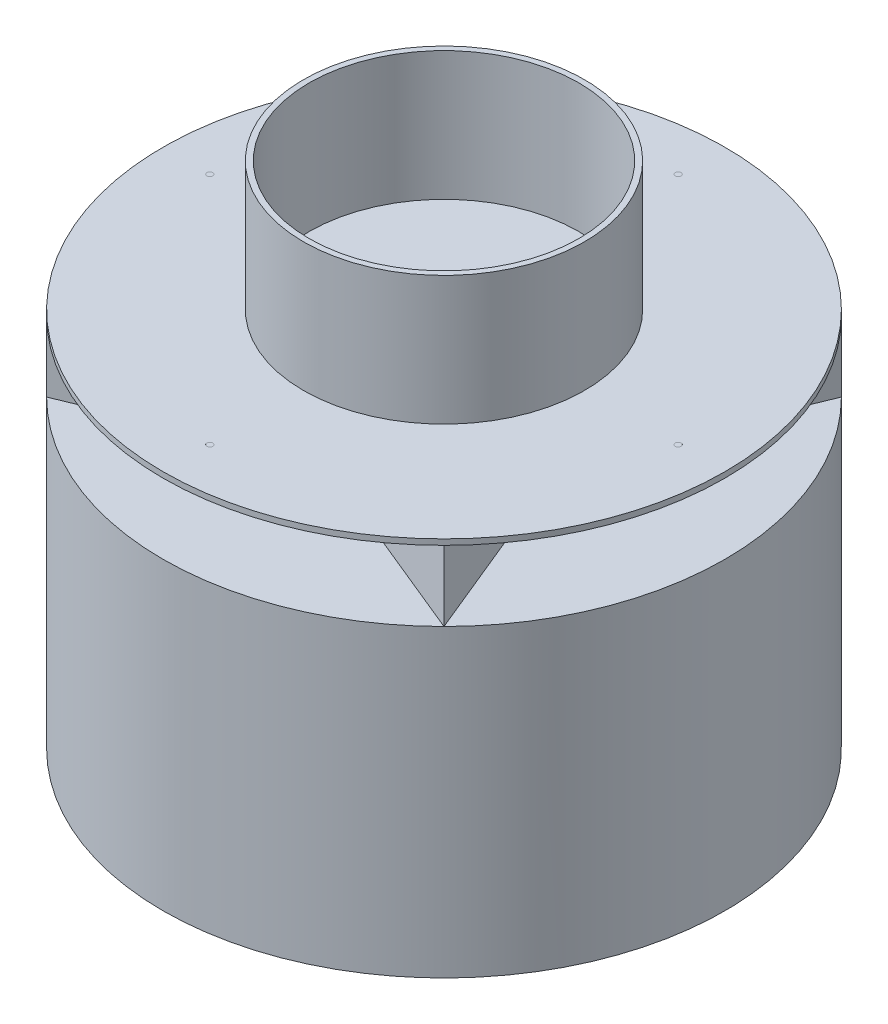
SolidWorks part; units mm, degrees
material "Plain Carbon Steel"
ref_plane "Front Plane" through (0, 0, 0) normal (0, 0, 1) x (1, 0, 0)
ref_plane "Top Plane" through (0, 0, 0) normal (0, 1, 0) x (1, 0, 0)
ref_plane "Right Plane" through (0, 0, 0) normal (1, 0, 0) x (0, 0, -1)
sketch "Sketch11" plane through (0, 0, 0) normal (0, 1, 0) x (1, 0, 0)
  circle A0 centre (0, 0) radius 304.8
extrude "Boss-Extrude5" add sketch "Sketch11" along normal blind 330.2
ref_plane "Plane3" through (0, 330.2, 0) normal (0, 1, 0) x (1, 0, 0)
sketch "Sketch12" plane through (0, 330.2, 0) normal (0, 1, 0) x (1, 0, 0)
  line L0 (-127, 0) -> (-215.5261, -215.5261)
  line L1 (127, 0) -> (215.5261, -215.5261)
  line L2 (-127, 0) -> (-215.5261, 215.5261)
  line L3 (-215.5261, -215.5261) -> (0, -127)
  line L4 (0, -127) -> (215.5261, -215.5261)
  line L5 (0, 127) -> (-215.5261, 215.5261)
  line L6 (0, 127) -> (215.5261, 215.5261)
  line L7 (215.5261, 215.5261) -> (127, 0)
  circle A0 centre (0, 0) radius 127
  circle A1 centre (0, 0) radius 304.8
extrude "Boss-Extrude6" add sketch "Sketch12" along normal blind 76.2 contours A0 | L4 A1 L3 A0
ref_plane "Plane4" through (0, 406.4, 0) normal (0, 1, 0) x (1, 0, 0)
sketch "Sketch13" plane through (0, 406.4, 0) normal (0, 1, 0) x (1, 0, 0)
  circle A0 centre (0, 0) radius 304.8
extrude "Boss-Extrude7" add sketch "Sketch13" along normal blind 6.096
ref_plane "Plane5" through (0, 412.496, 0) normal (0, 1, 0) x (1, 0, 0)
sketch "Sketch14" plane through (0, 412.496, 0) normal (0, 1, 0) x (1, 0, 0)
  circle A0 centre (0, 0) radius 152.4
  circle A1 centre (0, 0) radius 146.304
extrude "Boss-Extrude8" add sketch "Sketch14" along normal blind 139.7
ref_plane "Plane6" through (0, 412.496, 0) normal (0, 1, 0) x (1, 0, 0)
sketch "Sketch16" plane through (0, 412.496, 0) normal (0, 1, 0) x (1, 0, 0)
  circle A0 centre (0, 0) radius 304.8 construction
  circle A1 centre (254, 0) radius 3.175
  circle A2 centre (0, 254) radius 3.175
  circle A3 centre (0, -254) radius 3.175
  circle A4 centre (-254, 0) radius 3.175
  dimension "D1" = 6.35
  dimension "D2" = 6.35
  dimension "D3" = 6.35
  dimension "D4" = 6.35
  dimension "D5" = 254
  dimension "D6" = 254
  dimension "D7" = 254
  dimension "D8" = 254
extrude "Cut-Extrude2" cut sketch "Sketch16" against normal blind 0.0254
